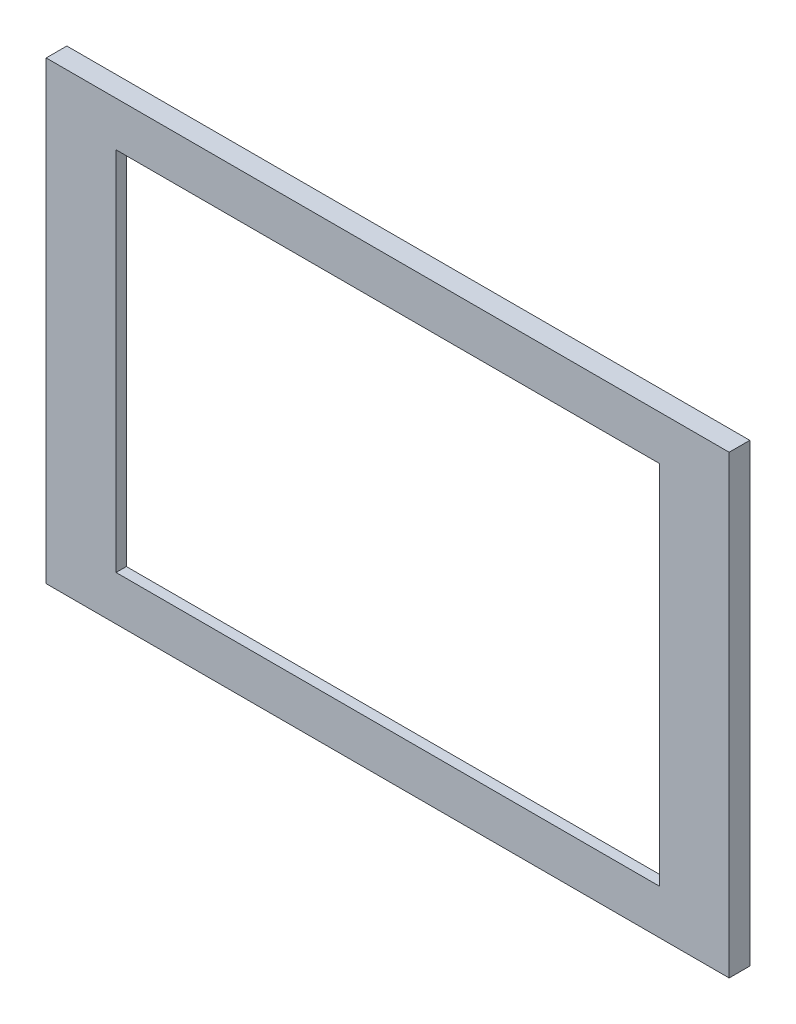
SolidWorks part; units mm, degrees
ref_plane "Front Plane" through (0, 0, 0) normal (0, 0, 1) x (1, 0, 0)
ref_plane "Top Plane" through (0, 0, 0) normal (0, 1, 0) x (1, 0, 0)
ref_plane "Right Plane" through (0, 0, 0) normal (1, 0, 0) x (0, 0, -1)
sketch "Sketch1" plane through (0, 0, 0) normal (0, 0, 1) x (1, 0, 0)
  line L0 (-10.5, -50.24) -> (-10.5, -56.04)
  line L1 (-41.76, -28.14) -> (41.76, -28.14)
  line L2 (-41.76, -28.14) -> (-41.76, 28.14)
  line L3 (-41.76, 28.14) -> (41.76, 28.14)
  line L4 (41.76, -28.14) -> (41.76, 28.14)
  line L5 (-41.76, -28.14) -> (41.76, 28.14) construction
  line L6 (-41.76, 28.14) -> (41.76, -28.14) construction
  line L7 (-56.76, 43.14) -> (56.76, 43.14)
  line L8 (-56.76, 43.14) -> (-56.76, -68.14)
  line L9 (-56.76, -68.14) -> (56.76, -68.14)
  line L10 (56.76, 43.14) -> (56.76, -68.14)
  line L11 (-25.5, -50.24) -> (-19.5, -50.24)
  line L12 (-25.5, -50.24) -> (-25.5, -56.04)
  line L13 (-25.5, -56.04) -> (-19.5, -56.04)
  line L14 (-19.5, -50.24) -> (-19.5, -56.04)
  line L15 (-41.76, -53.14) -> (41.76, -53.14) construction
  line L16 (-10.5, -50.24) -> (-4.5, -50.24)
  line L17 (-4.5, -50.24) -> (-4.5, -56.04)
  line L18 (-10.5, -56.04) -> (-4.5, -56.04)
  line L19 (4.5, -50.24) -> (4.5, -56.04)
  line L20 (4.5, -50.24) -> (10.5, -50.24)
  line L21 (10.5, -50.24) -> (10.5, -56.04)
  line L22 (4.5, -56.04) -> (10.5, -56.04)
  line L23 (19.5, -50.24) -> (19.5, -56.04)
  line L24 (19.5, -50.24) -> (25.5, -50.24)
  line L25 (25.5, -50.24) -> (25.5, -56.04)
  line L26 (19.5, -56.04) -> (25.5, -56.04)
  line L27 (-4.5, -53.14) -> (4.5, -53.14) construction
  line L28 (0, -68.14) -> (0, -53.44) construction
  line L29 (-4.5, -53.14) -> (4.5, -53.14) construction
  circle A0 centre (-41.76, -53.14) radius 8.5
  circle A1 centre (41.76, -53.14) radius 8.5
  point P0 (0, 0)
  point P16 (-25.5, -53.14)
  dimension "D12" = 17
  dimension "D13" = 17
  dimension "D1" = 56.28
  dimension "D2" = 83.52
  dimension "D3" = 15
  dimension "D4" = 15
  dimension "D5" = 113.52
  dimension "D6" = 15
  dimension "D7" = 40
  dimension "D8" = 15
  dimension "D9" = 15
  dimension "D10" = 15
  dimension "D11" = 15
  dimension "D14" = 6
  dimension "D15" = 5.8
  dimension "D16" = 4
extrude "Boss-Extrude1" add sketch "Sketch1" along normal blind 3.175
sketch "Sketch3" plane through (0, 0, 0) normal (0, 0, -1) x (-1, 0, 0)
  line L0 (41.76, 28.14) -> (41.76, -28.14) construction
  line L1 (41.76, -28.14) -> (-41.76, -28.14) construction
  line L2 (-41.76, -28.14) -> (-41.76, 28.14) construction
  line L3 (-41.76, 28.14) -> (41.76, 28.14) construction
  line L4 (41.76, 28.14) -> (41.76, -28.14)
  line L5 (41.76, -28.14) -> (-41.76, -28.14)
  line L6 (-41.76, -28.14) -> (-41.76, 28.14)
  line L7 (-41.76, 28.14) -> (41.76, 28.14)
  line L9 (-47.385, 30.54) -> (48.76, 30.54)
  line L10 (-47.385, 30.54) -> (-47.385, -30.54)
  line L11 (-47.385, -30.54) -> (48.76, -30.54)
  line L12 (48.76, 30.54) -> (48.76, -30.54)
  point P2 (0, 0)
  point P12 (45.71, 30.54)
  dimension "D1" = 5.625
  dimension "D2" = 61.08
  dimension "D3" = 7
  dimension "D4" = 2.4
extrude "Cut-Extrude1" cut sketch "Sketch3" against normal blind 1.5875
sketch "Sketch4" plane through (0, 0, 3.175) normal (0, 0, 1) x (1, 0, 0)
  line L1 (-52.5, 35) -> (52.5, 35)
  line L2 (-52.5, 35) -> (-52.5, -35)
  line L3 (-52.5, -35) -> (52.5, -35)
  line L4 (52.5, 35) -> (52.5, -35)
  line L5 (-52.5, 35) -> (52.5, -35) construction
  line L6 (-52.5, -35) -> (52.5, 35) construction
  line L10 (-56.76, 43.14) -> (-56.76, -68.14)
  line L11 (-56.76, -68.14) -> (56.76, -68.14)
  line L12 (56.76, -68.14) -> (56.76, 43.14)
  line L13 (56.76, 43.14) -> (-56.76, 43.14)
  line L14 (-56.76, 43.14) -> (-56.76, -68.14)
  line L15 (-56.76, -68.14) -> (56.76, -68.14)
  line L16 (56.76, -68.14) -> (56.76, 43.14)
  line L17 (56.76, 43.14) -> (-56.76, 43.14)
  point P0 (0, 0)
  dimension "D1" = 105
  dimension "D2" = 70
  dimension "D3" = 0
extrude "Cut-Extrude2" cut sketch "Sketch4" along direction (0, 0, 1) on the side against the normal blind 10
